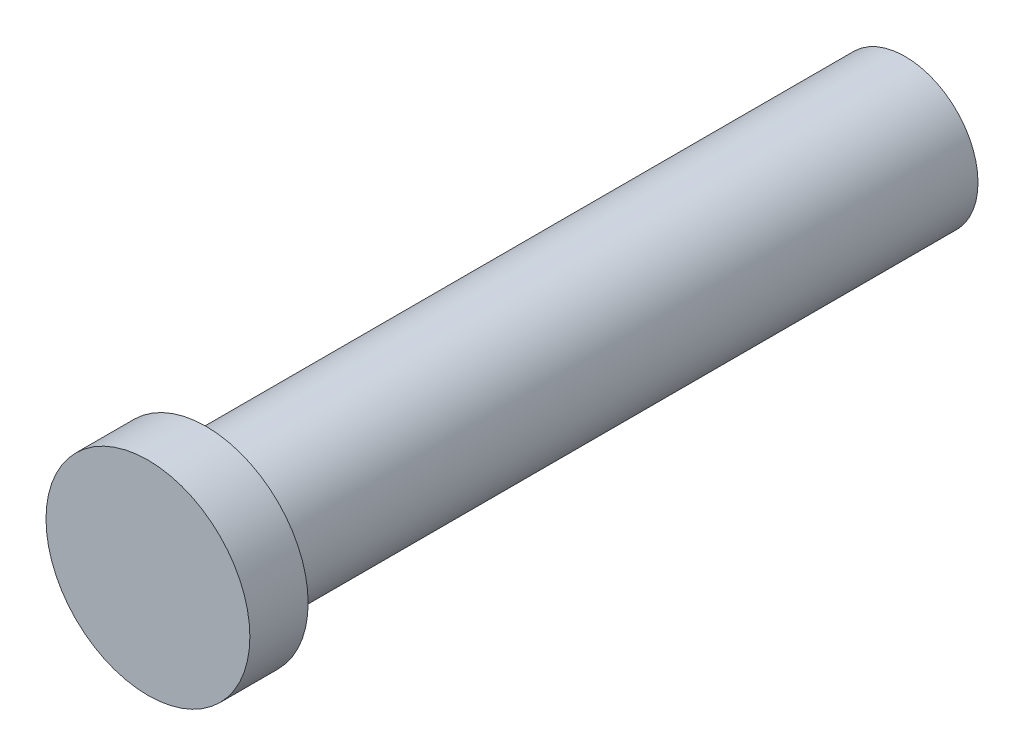
SolidWorks part; units mm, degrees
ref_plane "Front Plane" through (0, 0, 0) normal (0, 0, 1) x (1, 0, 0)
ref_plane "Top Plane" through (0, 0, 0) normal (0, 1, 0) x (1, 0, 0)
ref_plane "Right Plane" through (0, 0, 0) normal (1, 0, 0) x (0, 0, -1)
sketch "Sketch1" plane through (0, 0, 0) normal (0, 0, 1) x (1, 0, 0)
  circle A0 centre (0, 0) radius 1.25
extrude "Boss-Extrude1" add sketch "Sketch1" along normal blind 12
sketch "Sketch2" plane through (0, 0, 12) normal (0, 0, 1) x (1, 0, 0)
  circle A0 centre (0, 0) radius 1.75
extrude "Boss-Extrude2" add sketch "Sketch2" along normal blind 1
sketch "Sketch3" plane through (0, 0, 0) normal (0, 0, -1) x (-1, 0, 0)
  circle A0 centre (0, 0) radius 0.75
extrude "Cut-Extrude1" cut sketch "Sketch3" against normal blind 3
